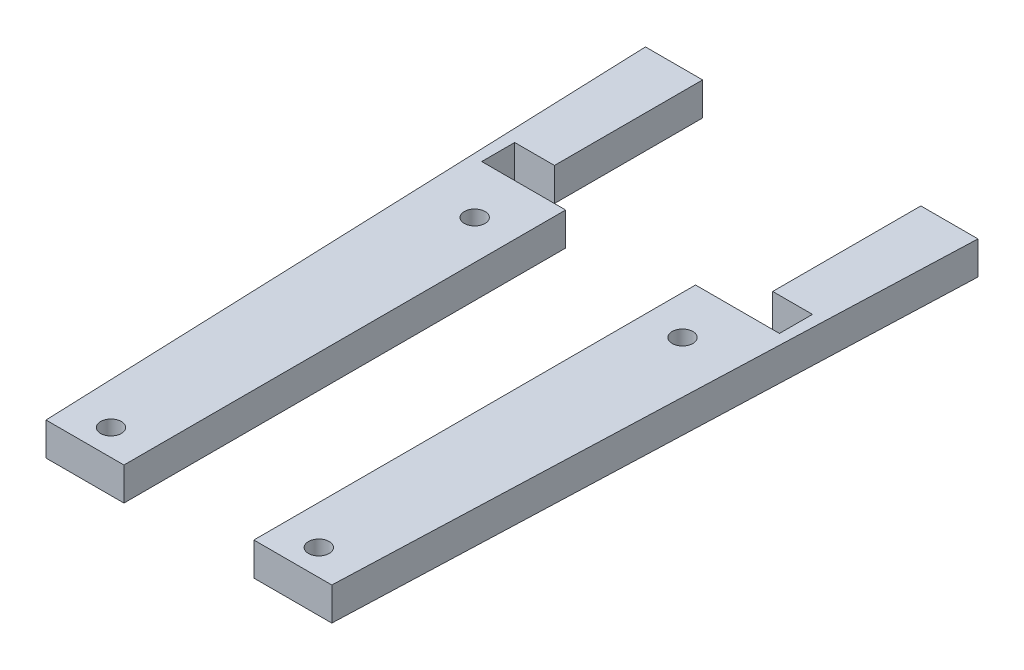
SolidWorks part; units mm, degrees
ref_plane "Front Plane" through (0, 0, 0) normal (0, 0, 1) x (1, 0, 0)
ref_plane "Top Plane" through (0, 0, 0) normal (0, 1, 0) x (1, 0, 0)
ref_plane "Right Plane" through (0, 0, 0) normal (1, 0, 0) x (0, 0, -1)
sketch "Sketch1" plane through (0, 0, 0) normal (0, 1, 0) x (1, 0, 0)
  line L0 (-35, 0) -> (-27.5, -199.8593)
  line L1 (-27.5, -199.8593) -> (27.5, -199.8593)
  line L2 (27.5, -199.8593) -> (35, 0)
  circle A0 centre (0, 0) radius 35
  point P3 (0, -199.8593)
  dimension "D1" = 70
  dimension "D2" = 55
  dimension "D3" = 200
extrude "Boss-Extrude1" add sketch "Sketch1" along normal mid plane 6.35
sketch "Sketch2" plane through (0, 3.175, 0) normal (0, 1, 0) x (1, 0, 0)
  line L0 (31.9979, -80) -> (-31.9979, -80)
  line L1 (27.5, -199.8593) -> (35, 0) construction
  line L2 (-35, 0) -> (-27.5, -199.8593) construction
  line M1 (27.5, -199.8593) -> (35, 0)
  arc M2 (35, 0) -> (-35, 0) centre (0, 0) ccw
  line M3 (-35, 0) -> (-27.5, -199.8593)
  dimension "D1" = 80
extrude "Cut-Extrude1" cut sketch "Sketch2" against normal through all contours L0 M1 M2 M3
fillet "Fillet2" [suppressed] radius 8
sketch "Sketch3" plane through (0, 3.175, 0) normal (0, 1, 0) x (1, 0, 0)
  line L0 (-27.5, -199.8593) -> (27.5, -199.8593) construction
  line L1 (21, -114.8593) -> (-21, -114.8593)
  line L2 (21, -114.8593) -> (21, -59.5093)
  line L3 (21, -59.5093) -> (-21, -59.5093)
  line L4 (-21, -114.8593) -> (-21, -59.5093)
  line L5 (21, -114.8593) -> (-21, -59.5093) construction
  line L6 (21, -59.5093) -> (-21, -114.8593) construction
  line L7 (12.5, -199.8593) -> (-12.5, -199.8593)
  line L8 (12.5, -199.8593) -> (12.5, -114.8593)
  line L9 (12.5, -114.8593) -> (-12.5, -114.8593)
  line L10 (-12.5, -199.8593) -> (-12.5, -114.8593)
  line L11 (12.5, -199.8593) -> (-12.5, -114.8593) construction
  line L12 (12.5, -114.8593) -> (-12.5, -199.8593) construction
  line L15 (-21, -114.8593) -> (-28.65, -114.8593)
  line L16 (-21, -114.8593) -> (-21, -108.5093)
  line L17 (-21, -108.5093) -> (-28.65, -108.5093)
  line L18 (-28.65, -114.8593) -> (-28.65, -108.5093)
  line L19 (21, -114.8593) -> (28.65, -114.8593)
  line L20 (21, -114.8593) -> (21, -108.5093)
  line L21 (21, -108.5093) -> (28.65, -108.5093)
  line L22 (28.65, -114.8593) -> (28.65, -108.5093)
  point P0 (0, -87.1843)
  point P5 (0, -157.3593)
  point P14 (0, -199.8593)
  line M12 (-27.5, -199.8593) -> (27.5, -199.8593)
  dimension "D1" = 85
  dimension "D2" = 25
  dimension "D3" = 55.35
  dimension "D4" = 42
  dimension "D5" = 6.35
  dimension "D6" = 7.65
extrude "Cut-Extrude2" cut sketch "Sketch3" against normal through all contours L4 L1 L2 L3 | L10 L8 L1 M12 | L18 L15 L4 L17 | L19 L22 L21 L2
sketch "Sketch4" plane through (0, 3.175, 0) normal (0, 1, 0) x (1, 0, 0)
  line L0 (29.0011, -159.8593) -> (-29.0011, -159.8593) construction
  line L1 (27.5, -199.8593) -> (31.9979, -80) construction
  line L2 (-31.9979, -80) -> (-27.5, -199.8593) construction
  line L3 (20, -194.8593) -> (-20, -194.8593) construction
  line L4 (0, -194.8593) -> (0, -159.8593) construction
  line L5 (28.65, -114.8593) -> (12.5, -114.8593) construction
  circle A2 centre (20, -194.8593) radius 2
  circle A3 centre (-20, -194.8593) radius 2
  circle A4 centre (-20, -124.8593) radius 2
  circle A5 centre (20, -124.8593) radius 2
  dimension "D2" = 40
  dimension "D4" = 4
  dimension "D1" = 35
  dimension "D3" = 80
extrude "Cut-Extrude3" cut sketch "Sketch4" against normal through all
